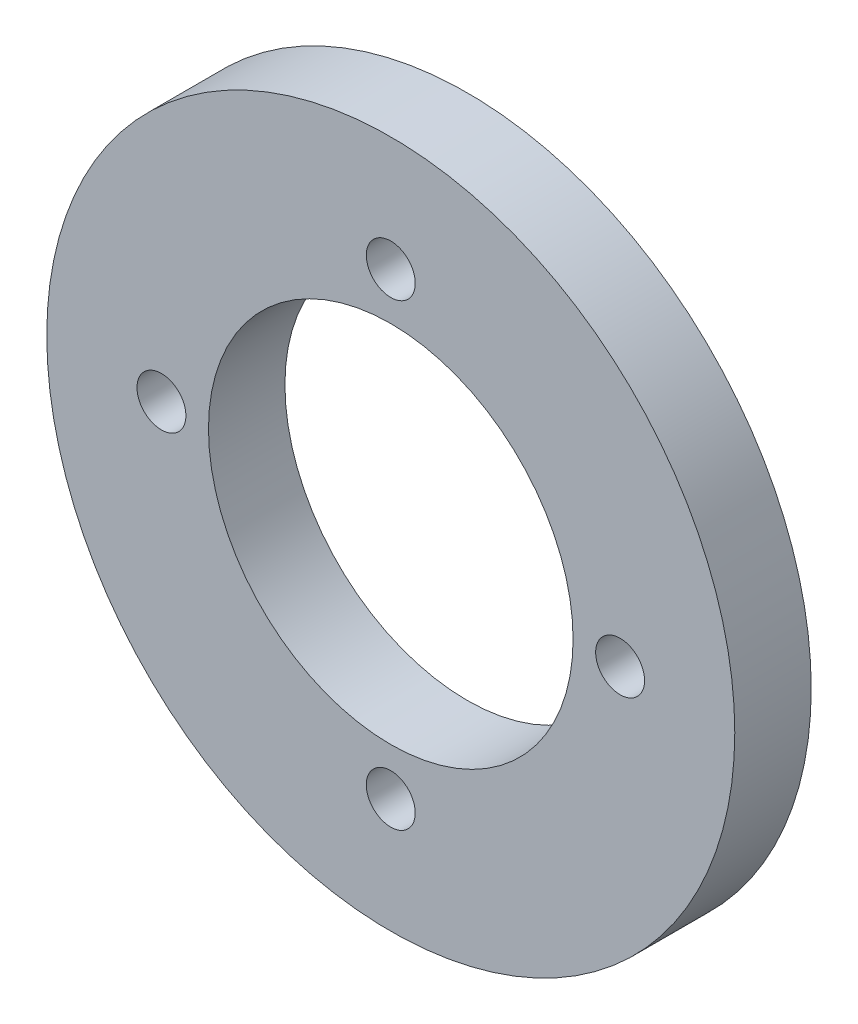
SolidWorks part; units mm, degrees
ref_plane "Front Plane" through (0, 0, 0) normal (0, 0, 1) x (1, 0, 0)
ref_plane "Top Plane" through (0, 0, 0) normal (0, 1, 0) x (1, 0, 0)
ref_plane "Right Plane" through (0, 0, 0) normal (1, 0, 0) x (0, 0, -1)
sketch "Sketch1" plane through (0, 0, 0) normal (0, 0, 1) x (1, 0, 0)
  circle A0 centre (0, 0) radius 22.5
  circle A1 centre (0, 0) radius 15 construction
  circle A2 centre (0, 15) radius 1.6
  circle A3 centre (15, 0) radius 1.6
  circle A4 centre (0, -15) radius 1.6
  circle A5 centre (-15, 0) radius 1.6
  circle A6 centre (0, 0) radius 11.9237
  point P15 (0, 0)
  dimension "D1" = 4
extrude "Boss-Extrude1" add sketch "Sketch1" along normal blind 5
